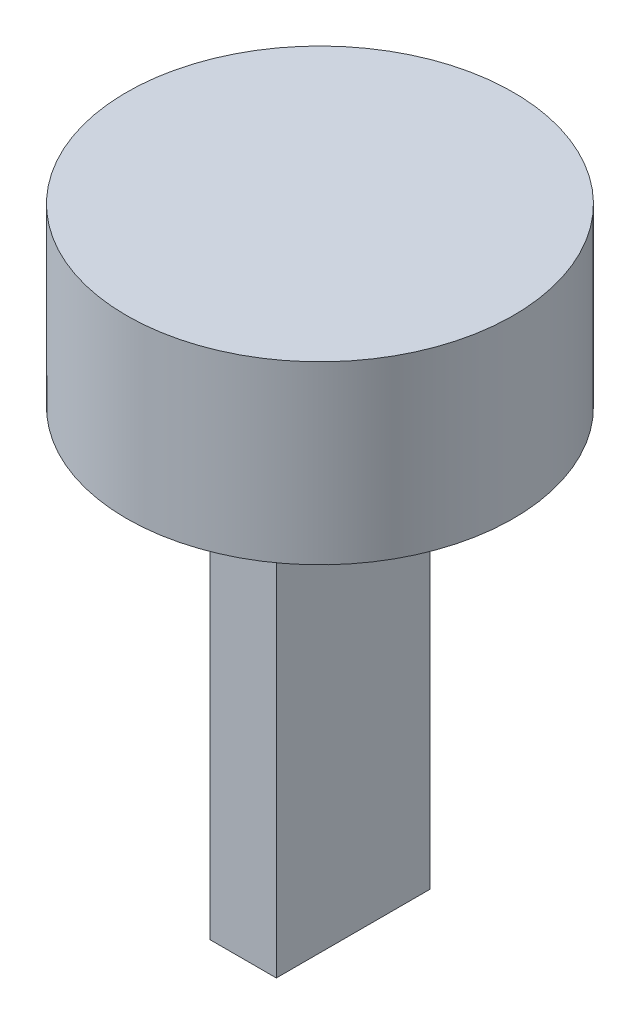
SolidWorks part; units mm, degrees
ref_plane "Front Plane" through (0, 0, 0) normal (0, 0, 1) x (1, 0, 0)
ref_plane "Top Plane" through (0, 0, 0) normal (0, 1, 0) x (1, 0, 0)
ref_plane "Right Plane" through (0, 0, 0) normal (1, 0, 0) x (0, 0, -1)
sketch "Sketch1" plane through (0, 0, 0) normal (0, 1, 0) x (1, 0, 0)
  line L1 (-0.6, 1.3875) -> (0.6, 1.3875)
  line L2 (-0.6, 1.3875) -> (-0.6, -1.3875)
  line L3 (-0.6, -1.3875) -> (0.6, -1.3875)
  line L4 (0.6, 1.3875) -> (0.6, -1.3875)
  line L5 (0, -1.3875) -> (0, 1.3875) construction
  line L6 (-0.6, 0) -> (0.6, 0) construction
  point P0 (0, 0)
  dimension "D1" = 1.2
  dimension "D2" = 2.775
extrude "Boss-Extrude1" add sketch "Sketch1" along normal blind 7.9375
sketch "Sketch2" plane through (0, 7.9375, 0) normal (0, 1, 0) x (1, 0, 0)
  circle A0 centre (0, 0) radius 3.4925
  dimension "D1" = 6.985
extrude "Boss-Extrude2" add sketch "Sketch2" along normal blind 3.175
